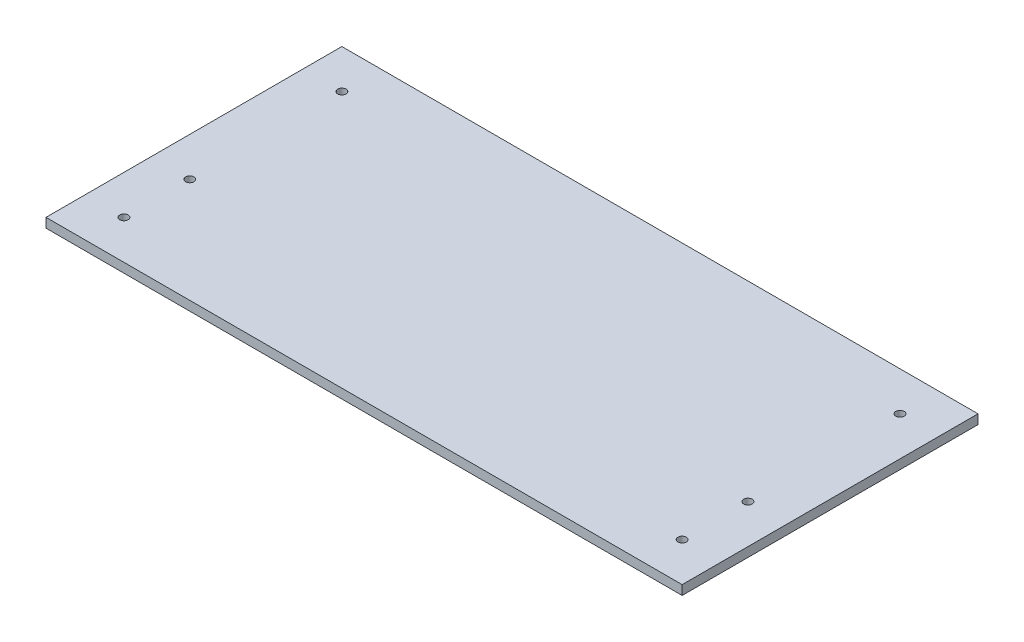
SolidWorks part; units mm, degrees
ref_plane "Front Plane" through (0, 0, 0) normal (0, 0, 1) x (1, 0, 0)
ref_plane "Top Plane" through (0, 0, 0) normal (0, 1, 0) x (1, 0, 0)
ref_plane "Right Plane" through (0, 0, 0) normal (1, 0, 0) x (0, 0, -1)
sketch "Sketch1" plane through (0, 0, 0) normal (0, 1, 0) x (1, 0, 0)
  line L1 (-107.505, -50) -> (107.505, -50)
  line L2 (-107.505, -50) -> (-107.505, 50)
  line L3 (-107.505, 50) -> (107.505, 50)
  line L4 (107.505, -50) -> (107.505, 50)
  line L5 (-107.505, -50) -> (107.505, 50) construction
  line L6 (-107.505, 50) -> (107.505, -50) construction
  point P0 (0, 0)
  dimension "D1" = 215.01
  dimension "D2" = 100
extrude "Boss-Extrude1" add sketch "Sketch1" along normal blind 3.18
sketch "Sketch2" plane through (0, 0, 0) normal (0, -1, 0) x (1, 0, 0)
  circle A1 centre (-94.325, -36.825) radius 1.4224
  circle A2 centre (-94.325, -36.825) radius 1.4224
  circle A3 centre (94.325, -36.82) radius 1.4224
  circle A4 centre (94.325, -36.82) radius 1.4224
  dimension "D1" = 0
  dimension "D2" = 0
extrude "Cut-Extrude1" cut sketch "Sketch2" against normal blind 3.18
mirror "Mirror1" about plane through (0, 0, 0) normal (0, 0, 1) of "Cut-Extrude1"
sketch "Sketch4" plane through (0, 0, 0) normal (0, -1, 0) x (1, 0, 0)
  circle A1 centre (-94.325, 14.58) radius 1.4224
  circle A2 centre (-94.325, 14.58) radius 1.4224
  circle A3 centre (94.325, 14.58) radius 1.4224
  circle A4 centre (94.325, 14.58) radius 1.4224
  dimension "D1" = 0
  dimension "D2" = 0
extrude "Cut-Extrude4" cut sketch "Sketch4" against normal blind 3.18
sketch "Sketch6" [suppressed] plane through (0, 0, 0) normal (0, -1, 0) x (1, 0, 0)
  line L0 (-47.5127, 45.22) -> (-47.5127, 35.22) construction
  line L1 (-47.5127, 45.22) -> (-47.5127, 34.72)
  line L2 (-35.5127, 35.22) -> (-35.5127, 45.22) construction
  line L3 (-47.0127, 34.72) -> (-36.0127, 34.72) construction
  line L4 (107.505, -50) -> (107.505, 50)
  line L5 (107.505, 50) -> (-107.505, 50)
  line L6 (-107.505, 50) -> (-107.505, -50)
  line L7 (-107.505, -50) -> (107.505, -50)
  line L8 (107.505, -50) -> (107.505, 50)
  line L9 (107.505, 50) -> (-107.505, 50)
  line L10 (-107.505, 50) -> (-107.505, -50)
  line L11 (-107.505, -50) -> (107.505, -50)
  line L12 (-35.5127, 34.72) -> (-35.5127, 45.22)
  line L13 (-47.5127, 34.72) -> (-35.5127, 34.72)
  line L14 (-47.0127, 45.22) -> (-36.0127, 45.22) construction
  line L15 (-47.5127, 45.22) -> (-35.5127, 45.22)
  dimension "D1" = 0
extrude "Cut-Extrude5" [suppressed] cut sketch "Sketch6" against normal blind 3.18
